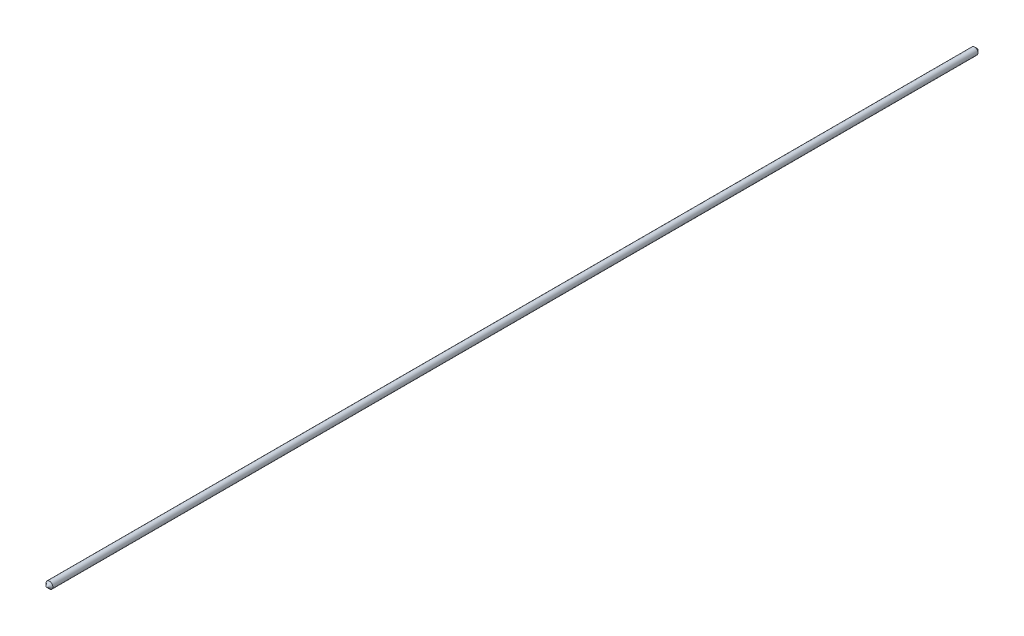
SolidWorks part; units mm, degrees
ref_plane "Front Plane" through (0, 0, 0) normal (0, 0, 1) x (1, 0, 0)
ref_plane "Top Plane" through (0, 0, 0) normal (0, 1, 0) x (1, 0, 0)
ref_plane "Right Plane" through (0, 0, 0) normal (1, 0, 0) x (0, 0, -1)
sketch "Sketch1" plane through (0, 0, 0) normal (1, 0, 0) x (0, 0, -1)
  line L0 (24.2766, 0) -> (34.1758, 10)
  line L1 (1527.0268, 0) -> (-1527.0268, 0) construction
  line L4 (34.1758, 10) -> (2743.6403, 10)
  line L5 (2743.6403, 10) -> (2753.7456, 0)
  line L6 (2753.7456, 0) -> (2057.6601, 0)
  line L8 (24.2766, 0) -> (2057.6601, 0)
  dimension "D1" = 45.29
  dimension "D2" = 44.7
  dimension "D3" = 2729.469
  dimension "D4" = 10
revolve "Revolve1" add sketch "Sketch1" angle 360 about L8
ref_plane "Plane1" through (0, 0, -24.2766) normal (0, 0, 1) x (1, 0, 0)
